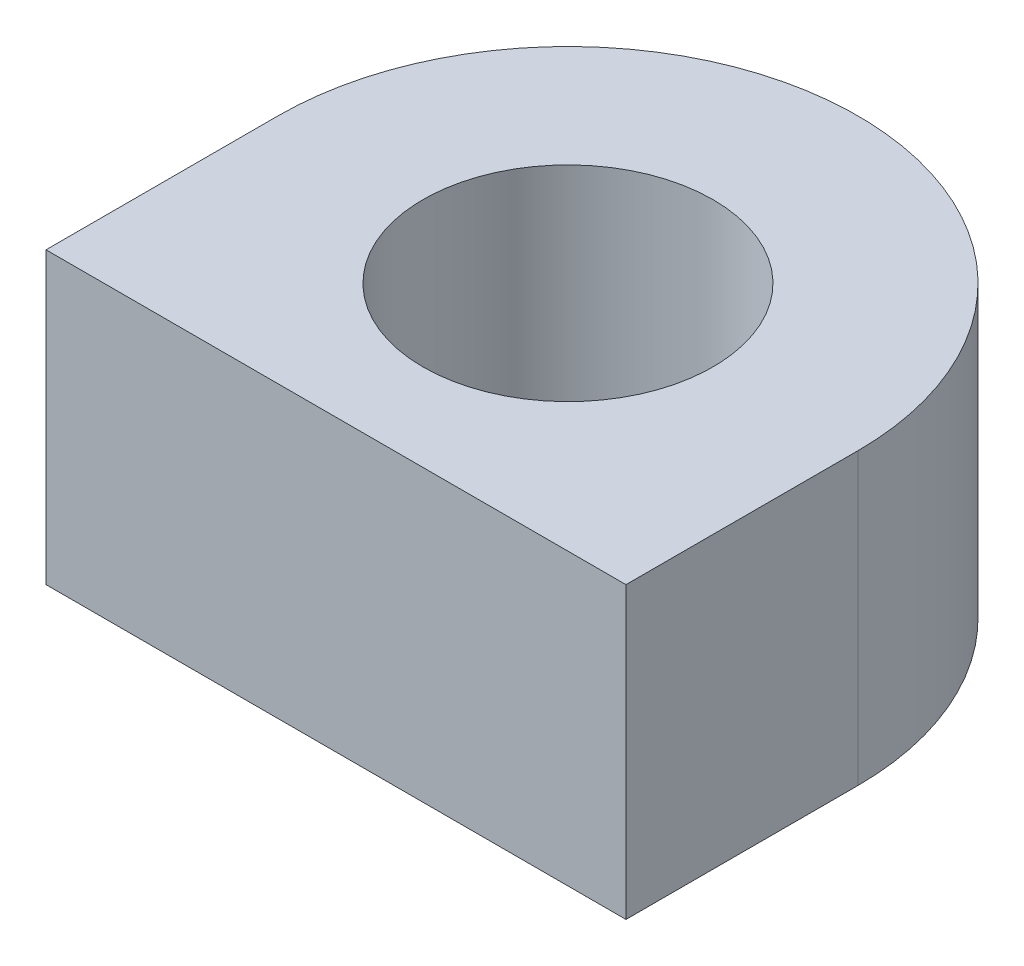
SolidWorks part; units mm, degrees
ref_plane "Front Plane" through (0, 0, 0) normal (0, 0, 1) x (1, 0, 0)
ref_plane "Top Plane" through (0, 0, 0) normal (0, 1, 0) x (1, 0, 0)
ref_plane "Right Plane" through (0, 0, 0) normal (1, 0, 0) x (0, 0, -1)
sketch "Sketch1" plane through (0, 0, 0) normal (0, 1, 0) x (1, 0, 0)
  line L0 (-10, -8) -> (-10, 0)
  line L1 (10, 0) -> (10, -8)
  line L2 (10, -8) -> (-10, -8)
  arc A0 (-10, 0) -> (10, 0) centre (0, 0) cw
  circle A1 centre (0, 0) radius 5
  dimension "D1" = 8
  dimension "D3" = 10
  dimension "D2" = 20
extrude "Boss-Extrude2" add sketch "Sketch1" along normal blind 10
